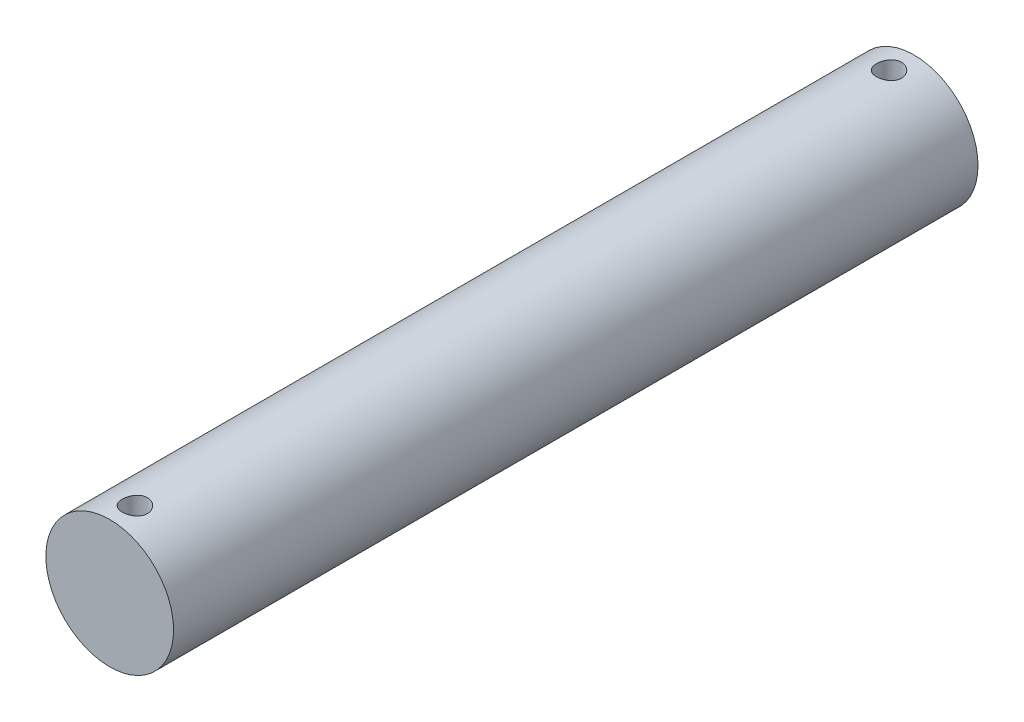
SolidWorks part; units mm, degrees
ref_plane "Front Plane" through (0, 0, 0) normal (0, 0, 1) x (1, 0, 0)
ref_plane "Top Plane" through (0, 0, 0) normal (0, 1, 0) x (1, 0, 0)
ref_plane "Right Plane" through (0, 0, 0) normal (1, 0, 0) x (0, 0, -1)
sketch "Sketch1" plane through (0, 0, 0) normal (0, 0, 1) x (1, 0, 0)
  circle A0 centre (0, 0) radius 6.35
  dimension "D1" = 12.7
extrude "Boss-Extrude1" add sketch "Sketch1" along normal mid plane 80 contours A0
sketch "Sketch2" plane through (0, 0, 0) normal (0, 1, 0) x (1, 0, 0)
  line L0 (-6.35, -40) -> (6.35, -40) construction
  line L1 (6.35, 40) -> (-6.35, 40) construction
  circle A0 centre (0, 37.5) radius 1.25
  circle A1 centre (0, -37.5) radius 1.25
  dimension "D2" = 2.5
  dimension "D4" = 2.5
  dimension "D1" = 2.5
  dimension "D3" = 2.5
extrude "Cut-Extrude1" cut sketch "Sketch2" against normal mid plane 50
